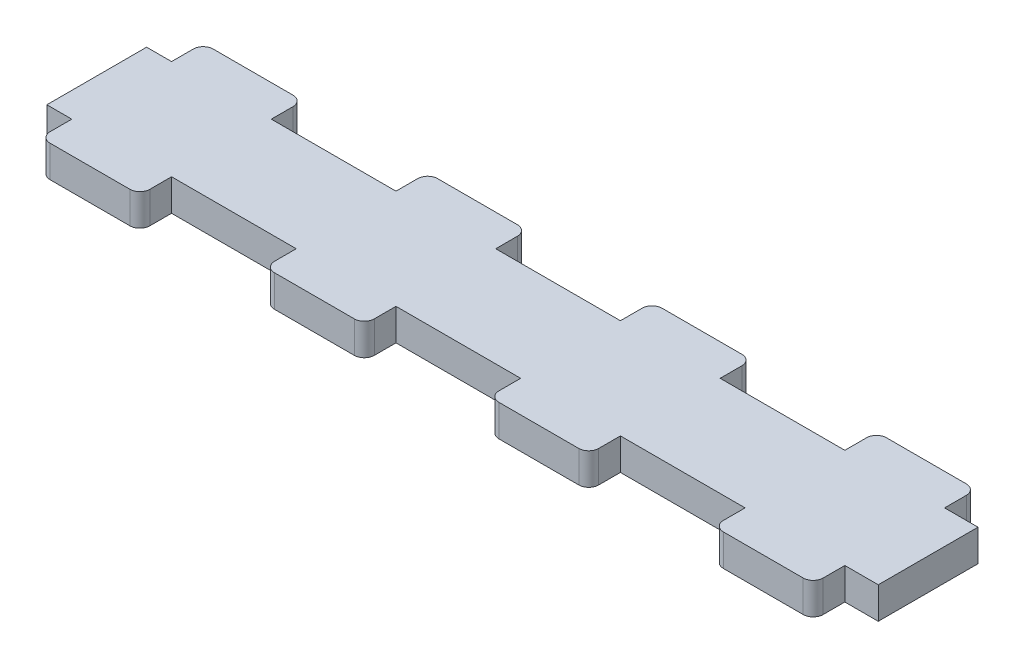
SolidWorks part; units mm, degrees
ref_plane "Front Plane" through (0, 0, 0) normal (0, 0, 1) x (1, 0, 0)
ref_plane "Top Plane" through (0, 0, 0) normal (0, 1, 0) x (1, 0, 0)
ref_plane "Right Plane" through (0, 0, 0) normal (1, 0, 0) x (0, 0, -1)
sketch "Sketch1" plane through (0, 0, 0) normal (0, 1, 0) x (1, 0, 0)
  line L0 (0, 0) -> (0, 10) construction
  line L1 (0, 0) -> (0, -10) construction
  line L2 (0, 0) -> (-166.7, 0) construction
  line L3 (0, 0) -> (16.5226, 0) construction
  line L4 (0, 0) -> (0, 10)
  line L5 (0, 10) -> (-6.7, 10)
  line L6 (-166.7, 10) -> (-166.7, 0)
  line L7 (-166.7, 0) -> (-166.7, -10)
  line L8 (-166.7, -10) -> (-161.7, -10)
  line L9 (-116.7, 10) -> (-116.7, 16.35)
  line L11 (-161.7, 10) -> (-161.7, 16.35)
  line L12 (-161.7, 16.35) -> (-141.7, 16.35)
  line L13 (-141.7, 10) -> (-141.7, 16.35)
  line L15 (-96.7, 10) -> (-96.7, 16.35)
  line L16 (-116.7, 16.35) -> (-96.7, 16.35)
  line L17 (-71.7, 10) -> (-71.7, 16.35)
  line L19 (-51.7, 10) -> (-51.7, 16.35)
  line L20 (-71.7, 16.35) -> (-51.7, 16.35)
  line L21 (-26.7, 10) -> (-26.7, 16.35)
  line L23 (-6.7, 10) -> (-6.7, 16.35)
  line L24 (-26.7, 16.35) -> (-6.7, 16.35)
  line L25 (-141.7, 10) -> (-116.7, 10) construction
  line L26 (-116.7, -10) -> (-116.7, -16.35)
  line L28 (-161.7, -10) -> (-161.7, -16.35)
  line L29 (-161.7, -16.35) -> (-141.7, -16.35)
  line L30 (-141.7, -10) -> (-141.7, -16.35)
  line L32 (-96.7, -10) -> (-96.7, -16.35)
  line L33 (-116.7, -16.35) -> (-96.7, -16.35)
  line L34 (-71.7, -10) -> (-71.7, -16.35)
  line L36 (-51.7, -10) -> (-51.7, -16.35)
  line L37 (-71.7, -16.35) -> (-51.7, -16.35)
  line L38 (-26.7, -10) -> (-26.7, -16.35)
  line L40 (-6.7, -10) -> (-6.7, -16.35)
  line L41 (-26.7, -16.35) -> (-6.7, -16.35)
  line L42 (-161.7, -10) -> (-116.7, -10) construction
  line L43 (-161.7, 10) -> (-166.7, 10)
  line L44 (-116.7, 10) -> (-141.7, 10)
  line L45 (-96.7, -10) -> (-71.7, -10)
  line L46 (0, 0) -> (0, -10)
  line L47 (-141.7, -10) -> (-116.7, -10)
  line L48 (-51.7, -10) -> (-26.7, -10)
  line L49 (-71.7, 10) -> (-96.7, 10)
  line L50 (-26.7, 10) -> (-51.7, 10)
  line L51 (-6.7, -10) -> (0, -10)
  dimension "D1" = 10
  dimension "D2" = 10
  dimension "D3" = 166.7
  dimension "D4" = 5
  dimension "D5" = 6.35
  dimension "D6" = 20
  dimension "D8" = 45
  dimension "D9" = 5
  dimension "D10" = 6.35
  dimension "D11" = 20
  dimension "D13" = 45
  dimension "D7" = 4
  dimension "D12" = 4
extrude "Boss-Extrude1" add sketch "Sketch1" along normal blind 6.35
fillet "Fillet1" radius 2 16 edges at (-161.7, 3.175, 16.35) (-141.7, 3.175, 16.35) (-116.7, 3.175, 16.35) (-96.7, 3.175, 16.35) (-71.7, 3.175, 16.35) (-51.7, 3.175, 16.35) (-26.7, 3.175, 16.35) (-6.7, 3.175, 16.35) (-6.7, 3.175, -16.35) (-26.7, 3.175, -16.35) (-71.7, 3.175, -16.35) (-51.7, 3.175, -16.35) (-96.7, 3.175, -16.35) (-116.7, 3.175, -16.35) (-141.7, 3.175, -16.35) (-161.7, 3.175, -16.35)
